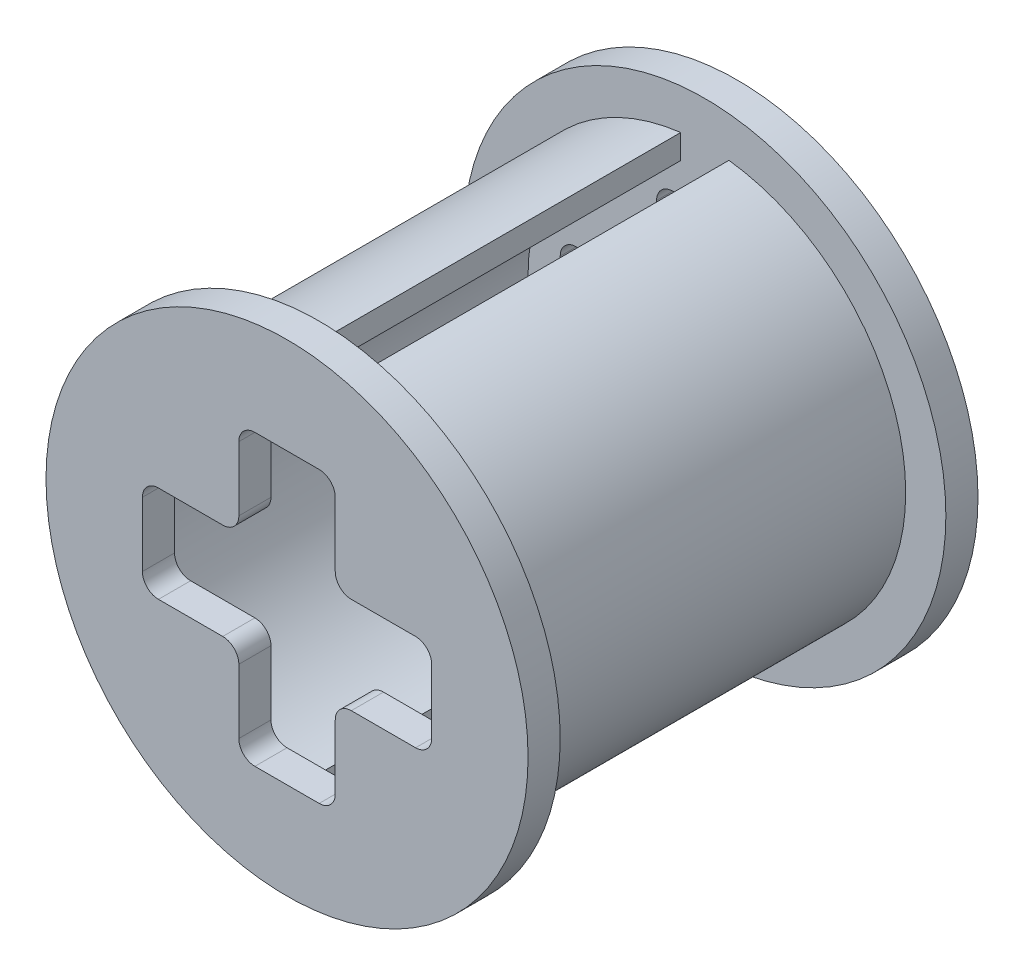
SolidWorks part; units mm, degrees
material "ABS PC"
ref_plane "Front Plane" through (0, 0, 0) normal (0, 0, 1) x (1, 0, 0)
ref_plane "Top Plane" through (0, 0, 0) normal (0, 1, 0) x (1, 0, 0)
ref_plane "Right Plane" through (0, 0, 0) normal (1, 0, 0) x (0, 0, -1)
sketch "Sketch1" plane through (0, 0, 0) normal (0, 1, 0) x (1, 0, 0)
  line L0 (-8.001, 3.556) -> (0, 3.556)
  line L1 (-8.001, -3.556) -> (0, -3.556)
  circle A0 centre (0, 0) radius 2.286 construction
  arc A1 (0, -3.556) -> (0, 3.556) centre (0, 0) ccw
  arc A2 (-8.001, 3.556) -> (-8.001, -3.556) centre (-8.001, 0) ccw
  dimension "D1" = 7.112
  dimension "D2" = 4.572
  dimension "D3" = 8.001
extrude "Extrude1" add sketch "Sketch1" along normal blind 3.81
ref_plane "Plane1" through (0, 0, 3.556) normal (0, 0, 1) x (1, 0, 0)
sketch "Sketch4" plane through (0, 0, 3.556) normal (0, 0, 1) x (1, 0, 0)
  line L0 (0, 0) -> (0, 3.81)
  line L2 (0, 3.81) -> (7.112, 3.81)
  line L4 (7.112, 0) -> (0, 0)
  line L5 (7.112, 0) -> (10.922, 0)
  arc A0 (10.922, 0) -> (7.112, 3.81) centre (7.112, 0) ccw
  dimension "D2" = 3.81
  dimension "D1" = 7.112
extrude "Extrude2" add sketch "Sketch4" against normal blind 0.508
sketch "Sketch6" plane through (0, 0, 3.556) normal (0, 0, 1) x (1, 0, 0)
  line L0 (6.35, 2.032) -> (6.35, 1.016)
  line L1 (6.096, 0.762) -> (5.08, 0.762)
  line L2 (4.826, 0.508) -> (4.826, -0.508)
  line L3 (5.08, -0.762) -> (6.096, -0.762)
  line L4 (6.35, -1.016) -> (6.35, -2.032)
  line L5 (6.604, -2.286) -> (7.62, -2.286)
  line L6 (7.874, -2.032) -> (7.874, -1.016)
  line L7 (8.128, -0.762) -> (9.144, -0.762)
  line L8 (9.398, -0.508) -> (9.398, 0.508)
  line L9 (9.144, 0.762) -> (8.128, 0.762)
  line L10 (7.874, 1.016) -> (7.874, 2.032)
  line L11 (7.62, 2.286) -> (6.604, 2.286)
  line L12 (7.112, 1.454) -> (7.112, -1.454) construction
  line L13 (3.4212, 0) -> (10.8028, 0) construction
  arc A0 (6.35, 1.016) -> (6.096, 0.762) centre (6.096, 1.016) cw
  arc A1 (6.35, 2.032) -> (6.604, 2.286) centre (6.604, 2.032) cw
  arc A2 (7.62, 2.286) -> (7.874, 2.032) centre (7.62, 2.032) cw
  arc A3 (7.874, 1.016) -> (8.128, 0.762) centre (8.128, 1.016) ccw
  arc A4 (9.144, 0.762) -> (9.398, 0.508) centre (9.144, 0.508) cw
  arc A5 (9.144, -0.762) -> (9.398, -0.508) centre (9.144, -0.508) ccw
  arc A6 (8.128, -0.762) -> (7.874, -1.016) centre (8.128, -1.016) ccw
  arc A7 (7.874, -2.032) -> (7.62, -2.286) centre (7.62, -2.032) cw
  arc A8 (6.604, -2.286) -> (6.35, -2.032) centre (6.604, -2.032) cw
  arc A9 (6.096, -0.762) -> (6.35, -1.016) centre (6.096, -1.016) cw
  arc A10 (5.08, -0.762) -> (4.826, -0.508) centre (5.08, -0.508) cw
  arc A11 (4.826, 0.508) -> (5.08, 0.762) centre (5.08, 0.508) cw
  arc A13 (10.922, 0) -> (7.112, 3.81) centre (7.112, 0) ccw construction
  point P40 (7.112, 0)
  dimension "D6" = 0.254
  dimension "D1" = 4.572
  dimension "D2" = 4.572
  dimension "D3" = 1.524
  dimension "D4" = 1.524
  dimension "D5" = 1.524
extrude "Cut-Extrude2" cut sketch "Sketch6" against normal through all
sketch "Sketch8" plane through (0, 0, 3.048) normal (0, 0, -1) x (-1, 0, 0)
  line L0 (-10.287, 0) -> (-9.906, 0)
  line L1 (-4.318, 0) -> (-3.937, 0)
  line L2 (-7.112, 0) -> (-7.112, 5.3462) construction
  line L4 (-7.493, 2.7679) -> (-7.493, 3.1521)
  line L6 (-6.731, 2.7679) -> (-6.731, 3.1521)
  arc A0 (-3.937, 0) -> (-6.731, 3.1521) centre (-7.112, 0) ccw
  arc A1 (-4.318, 0) -> (-6.731, 2.7679) centre (-7.112, 0) ccw
  arc A2 (-7.493, 3.1521) -> (-10.287, 0) centre (-7.112, 0) ccw
  arc A3 (-7.493, 2.7679) -> (-9.906, 0) centre (-7.112, 0) ccw
  dimension "D1" = 5.588
  dimension "D2" = 6.35
  dimension "D3" = 0.762
extrude "Extrude3" add sketch "Sketch8" along normal blind 3.048
sketch "Sketch9" plane through (0, 0, 0) normal (0, 0, -1) x (-1, 0, 0)
  line L0 (-4.318, 0) -> (-3.937, 0) construction
  line L2 (-4.1275, 0) -> (-1.0818, 0)
  line L3 (-4.1275, 0) -> (-4.1275, 0.1905)
  line L4 (-4.1275, 0.1905) -> (-1.0818, 0.1905)
  line L5 (-1.0818, 0) -> (-1.0818, 0.1905)
  dimension "D1" = 0.1905
extrude "Extrude4" add sketch "Sketch9" against normal through all
mirror "Mirror5" about plane through (7.112, 0, 0) normal (0, 0, -1) of "Cut-Extrude2", "Extrude3", "Extrude2", "Extrude4"
sketch "Sketch11" plane through (0, 3.81, 0) normal (0, 1, 0) x (1, 0, 0)
  circle A0 centre (0, 0) radius 2.286
  circle A1 centre (-8.001, 0) radius 2.286
  arc A2 (-8.001, 3.556) -> (-8.001, -3.556) centre (-8.001, 0) ccw construction
  dimension "D1" = 4.572
extrude "Cut-Extrude3" cut sketch "Sketch11" against normal through all
sketch "Sketch12" plane through (0, 3.81, 0) normal (0, 1, 0) x (1, 0, 0)
  circle A0 centre (0, 0) radius 3.175
  circle A1 centre (-8.001, 0) radius 3.175
  dimension "D1" = 6.35
extrude "Cut-Extrude4" cut sketch "Sketch12" against normal blind 0.508
mirror "Mirror6" of bodies 108
sketch "Sketch13" plane through (0, 0, 3.556) normal (0, 0, 1) x (1, 0, 0)
  circle A0 centre (7.112, 0) radius 3.81
extrude "Cut-Extrude5" cut sketch "Sketch13" against normal through all flip side to cut
sketch "Sketch15" plane through (0, 0, -3.048) normal (0, 0, 1) x (1, 0, 0)
  line L1 (4.1587, 2.4071) -> (5.0416, 2.4071)
  line L3 (4.1587, -2.4071) -> (5.0416, -2.4071)
  arc A0 (4.1587, 2.4071) -> (4.1587, -2.4071) centre (7.112, 0) ccw
  arc A1 (5.0416, 2.4071) -> (5.0416, -2.4071) centre (7.112, 0) ccw
extrude "Cut-Extrude7" cut sketch "Sketch15" along normal up to surface (6.096 mm away) up to face at (7.112, 0, 3.048)
